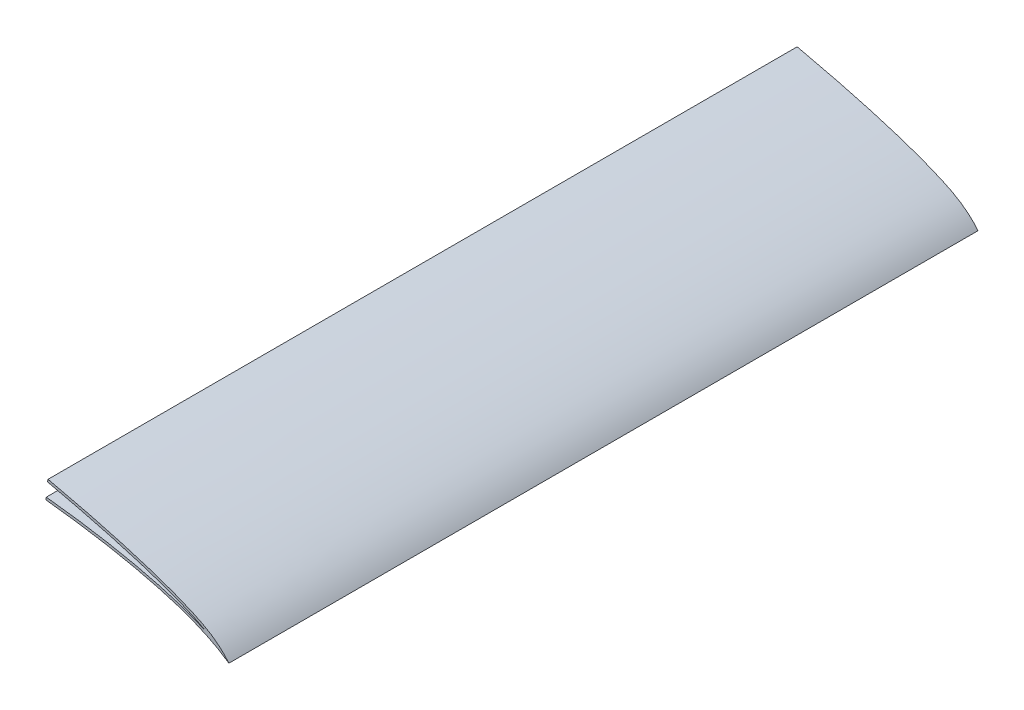
SolidWorks part; units mm, degrees
material "Balsa"
ref_plane "Front Plane" through (0, 0, 0) normal (0, 0, 1) x (1, 0, 0)
ref_plane "Top Plane" through (0, 0, 0) normal (0, 1, 0) x (1, 0, 0)
ref_plane "Right Plane" through (0, 0, 0) normal (1, 0, 0) x (0, 0, -1)
sketch "Sketch1" plane through (0, 0, 319.6812) normal (0, 0, -1) x (-1, 0, 0)
  line L0 (-584.2464, 388.1682) -> (-584.593, 389.7174)
  line L1 (-583.5103, 379.7411) -> (-583.3391, 378.1629)
  spline S0 degree 3 poles (-188.3068, -512.699) (-824.9774, 226.0667) (-753.4412, 335.7272) (-653.4368, 367.4388) (-633.0799, 372.3244) (-346.3926, 423.2883) (-37.0733, 243.6474) (-35.0032, 1215.8831) knots 0.379421 0.379421 0.379421 0.379421 0.826141 0.846447 0.887057 0.927667 2.260799 2.260799 2.260799 2.260799 only from (-681.1024, 357.442) to (-583.5103, 379.7411) construction
  spline S1 degree 3 poles (-246.1939, 1329.2951) (15.4967, 371.6767) (-327.8755, 458.0969) (-629.6987, 376.8578) (-645.9629, 371.8758) (-658.0289, 367.7686) (-667.898, 363.9148) (-723.6555, 338.8156) (-745.9555, 279.3309) (-608.4556, -639.9138) knots -1.335963 -1.335963 -1.335963 -1.335963 0.071019 0.110982 0.130963 0.150944 0.170926 0.180916 0.439829 0.439829 0.439829 0.439829 only from (-584.2464, 388.1682) to (-681.1024, 357.442) construction
  spline S2 degree 3 poles (-681.1024, 357.442) (-677.2828, 359.2195) (-669.4373, 362.365) (-653.4368, 367.4388) (-633.0799, 372.3244) (-608.3849, 376.7144) (-591.8137, 378.8401) (-583.5103, 379.7411) knots 0.805836 0.805836 0.805836 0.805836 0.826141 0.846447 0.887057 0.927667 0.968278 0.968278 0.968278 0.968278
  spline S3 degree 3 poles (-584.2464, 388.1682) (-592.5586, 386.3087) (-609.1427, 382.3906) (-629.6987, 376.8578) (-645.9629, 371.8758) (-658.0289, 367.7686) (-667.898, 363.9148) (-675.6111, 360.4427) (-679.3042, 358.5072) (-681.1024, 357.442) knots 0.031057 0.031057 0.031057 0.031057 0.071019 0.110982 0.130963 0.150944 0.170926 0.180916 0.190907 0.190907 0.190907 0.190907
  spline S4 degree 1 poles (-584.593, 389.7174) (-694.9609, 347.6781) knots 0 0 1 1 construction
  spline S5 degree 1 poles (-694.9609, 347.6781) (-583.3391, 378.1629) knots 0 0 1 1 construction
  spline S6 degree 3 poles (-584.593, 389.7174) (-594.239, 387.5596) (-608.6651, 384.1258) (-627.7626, 379.0008) (-641.9858, 374.8157) (-653.7284, 370.9551) (-663.0042, 367.5379) (-669.8771, 364.7631) (-676.6545, 361.7278) (-682.0877, 358.814) (-686.2641, 356.0118) (-689.2936, 353.6213) (-691.723, 351.3385) (-693.5932, 349.3221) (-694.5165, 348.2293) (-694.9609, 347.6781) knots 0.031057 0.031057 0.031057 0.031057 0.077353 0.100501 0.12365 0.146798 0.158372 0.169946 0.18152 0.193094 0.198881 0.204668 0.210455 0.213349 0.216242 0.216242 0.216242 0.216242
  spline S7 degree 3 poles (-694.9609, 347.6781) (-691.029, 350.4672) (-682.6713, 355.2953) (-669.0983, 360.8591) (-655.1504, 365.2064) (-636.2688, 370.0041) (-612.3343, 374.5633) (-593.0194, 377.1124) (-583.3391, 378.1629) knots 0.778365 0.778365 0.778365 0.778365 0.802104 0.825843 0.849582 0.873321 0.9208 0.968278 0.968278 0.968278 0.968278
  dimension "D1" = 1.5875
extrude "Boss-Extrude1" add sketch "Sketch1" against normal up to vertex (457.2 mm away)
